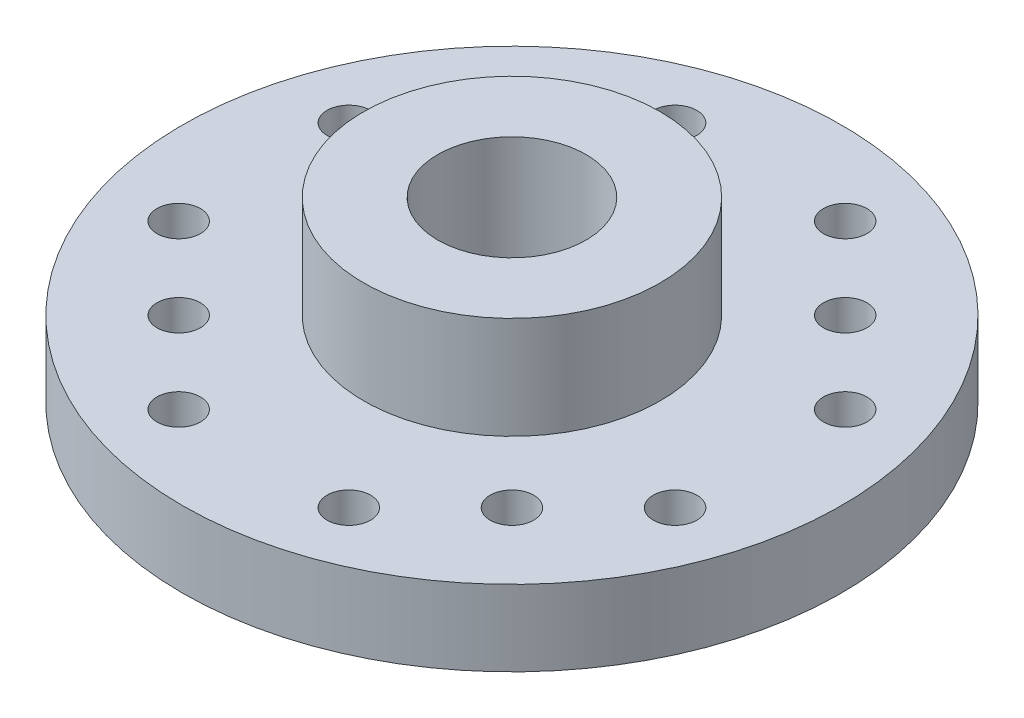
SolidWorks part; units mm, degrees
ref_plane "Front Plane" through (0, 0, 0) normal (0, 0, 1) x (1, 0, 0)
ref_plane "Top Plane" through (0, 0, 0) normal (0, 1, 0) x (1, 0, 0)
ref_plane "Right Plane" through (0, 0, 0) normal (1, 0, 0) x (0, 0, -1)
sketch "Sketch1" plane through (0, 0, 0) normal (0, 1, 0) x (1, 0, 0)
  line L0 (-5.0558, 5.0558) -> (5.0558, 5.0558) construction
  line L1 (5.0558, 5.0558) -> (5.0558, -5.0558) construction
  circle A0 centre (0, 0) radius 10
  circle A1 centre (-5.0558, 5.0558) radius 0.66
  circle A2 centre (5.0558, 5.0558) radius 0.66
  circle A3 centre (5.0558, -5.0558) radius 0.66
  circle A4 centre (-5.0558, -5.0558) radius 0.66
  circle A5 centre (0, 0) radius 7.15 construction
  circle A6 centre (0, 0) radius 1.5
  dimension "D1" = 20
  dimension "D2" = 1.32
  dimension "D3" = 3
  dimension "D4" = 14.3
extrude "Boss-Extrude1" add sketch "Sketch1" along normal blind 2.3
sketch "Sketch2" plane through (0, 2.3, 0) normal (0, 1, 0) x (1, 0, 0)
  circle A0 centre (0, 0) radius 4.5
  circle A1 centre (0, 0) radius 1.5 construction
  circle A2 centre (0, 0) radius 1.5
  dimension "D1" = 9
extrude "Boss-Extrude2" add sketch "Sketch2" along normal blind 3.1
sketch "Sketch3" plane through (0, 5.4, 0) normal (0, 1, 0) x (1, 0, 0)
  circle A0 centre (0, 0) radius 2.25
  dimension "D1" = 4.5
extrude "Cut-Extrude1" cut sketch "Sketch3" against normal blind 3.6
sketch "ｽｹｯﾁ1" plane through (0, 0, 0) normal (0, -1, 0) x (-1, 0, 0)
  line L1 (0, -10.1116) -> (10.1116, 0) construction
  line L2 (10.1116, 0) -> (0, 10.1116) construction
  line L3 (0, 10.1116) -> (-10.1116, 0) construction
  line L4 (-10.1116, 0) -> (0, -10.1116) construction
  circle A0 centre (0, 0) radius 7.15 construction
  circle A2 centre (-2.5809, -7.5307) radius 0.66
  circle A3 centre (-7.5307, -2.5809) radius 0.66
  circle A4 centre (-5.0558, -5.0558) radius 0.66 construction
  circle A5 centre (-7.5307, 2.5809) radius 0.66
  circle A6 centre (-2.5809, 7.5307) radius 0.66
  circle A7 centre (2.5809, 7.5307) radius 0.66
  circle A8 centre (7.5307, 2.5809) radius 0.66
  circle A9 centre (7.5307, -2.5809) radius 0.66
  circle A10 centre (2.5809, -7.5307) radius 0.66
  circle A11 centre (-5.0558, 5.0558) radius 0.66 construction
  circle A13 centre (5.0558, 5.0558) radius 0.66 construction
  circle A14 centre (5.0558, -5.0558) radius 0.66 construction
  dimension "D2" = 3.5
  dimension "D3" = 3.5
  dimension "D4" = 3.5
  dimension "D5" = 3.5
  dimension "D6" = 3.5
  dimension "D7" = 3.5
  dimension "D8" = 3.5
  dimension "D9" = 3.5
  dimension "D1" = 7.15
extrude "ｶｯﾄ - 押し出し1" cut sketch "ｽｹｯﾁ1" against normal through all
sketch "ｽｹｯﾁ2" plane through (0, 0, 0) normal (0, -1, 0) x (-1, 0, 0)
  circle A0 centre (0, 0) radius 2.7
  circle A1 centre (0, 0) radius 3.2
  circle A2 centre (0, 0) radius 4.375
  circle M15 centre (0, 0) radius 1.5
  dimension "D1" = 5.4
  dimension "D2" = 8.75
  dimension "D3" = 0.5
extrude "ｶｯﾄ - 押し出し2" cut sketch "ｽｹｯﾁ2" against normal blind 0.8 contours A0 M15 | A2 A1
